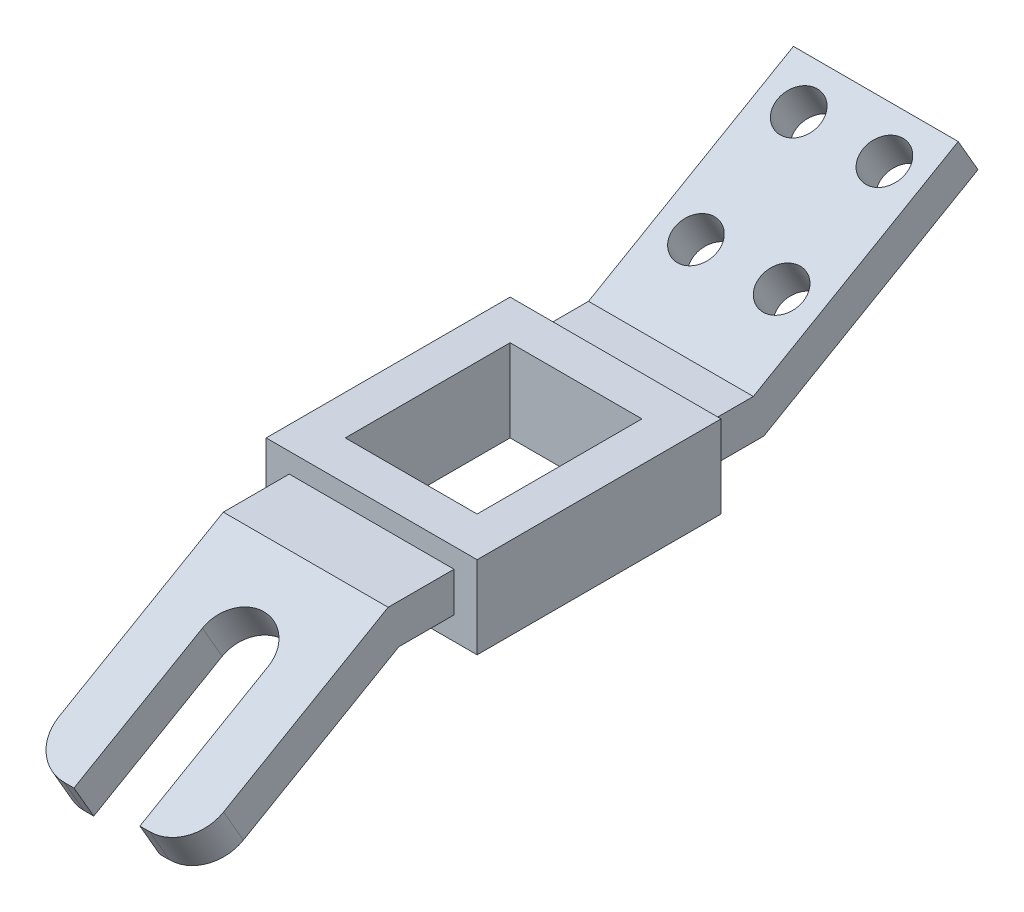
SolidWorks part; units mm, degrees
ref_plane "Alzado" through (0, 0, 0) normal (0, 0, 1) x (1, 0, 0)
ref_plane "Planta" through (0, 0, 0) normal (0, 1, 0) x (1, 0, 0)
ref_plane "Vista lateral" through (0, 0, 0) normal (1, 0, 0) x (0, 0, -1)
sketch "Croquis1" plane through (0, 0, 0) normal (0, 1, 0) x (1, 0, 0)
  line L1 (-32, 37) -> (32, 37)
  line L2 (-32, 37) -> (-32, -37)
  line L3 (-32, -37) -> (32, -37)
  line L4 (32, 37) -> (32, -37)
  line L5 (-20, 25) -> (20, 25)
  line L6 (-20, 25) -> (-20, -25)
  line L7 (-20, -25) -> (20, -25)
  line L8 (20, 25) -> (20, -25)
  point P4 (32, 0)
  point P5 (0, -37)
  point P11 (0, 25)
  point P12 (20, 0)
  dimension "D1" = 74
  dimension "D2" = 64
  dimension "D3" = 40
  dimension "D4" = 50
  dimension "D5" = 12
  dimension "D6" = 12
extrude "Saliente-Extruir2" add sketch "Croquis1" along normal blind 25
ref_plane "Plano1" through (0, 0, 0) normal (1, 0, 0) x (0, 0, -1)
sketch "Croquis2" plane through (0, 0, 0) normal (1, 0, 0) x (0, 0, -1)
  line L0 (37, 19) -> (53.7846, 19)
  line L1 (37, 25) -> (37, 0) construction
  line L2 (53.7846, 19) -> (115.9519, 54.8923)
  line L3 (115.9519, 54.8923) -> (121.9519, 44.5)
  line L4 (121.9519, 44.5) -> (57, 7)
  line L5 (57, 7) -> (37, 7)
  line L6 (-37, 25) -> (37, 25) construction
  line L7 (37, 19) -> (37, 7)
  line L8 (-37, 19) -> (-57, 19)
  line L9 (-37, 25) -> (-37, 0) construction
  line L10 (-57, 19) -> (-117.3124, -15.8214)
  line L11 (-117.3124, -15.8214) -> (-111.3124, -26.2137)
  line L12 (-111.3124, -26.2137) -> (-53.7846, 7)
  line L13 (-53.7846, 7) -> (-37, 7)
  line L14 (-37, 19) -> (-37, 7)
  dimension "D1" = 30
  dimension "D2" = 12
  dimension "D3" = 6
  dimension "D4" = 20
  dimension "D5" = 75
  dimension "D6" = 12
  dimension "D7" = 12
  dimension "D8" = 20
  dimension "D9" = 69.6428
  dimension "D10" = 30
  dimension "D11" = 12
extrude "Saliente-Extruir3" add sketch "Croquis2" along normal mid plane 50
sketch "Croquis3" plane through (0, -9.0394, -5.2189) normal (0, 0.866, 0.5) x (1, 0, 0)
  line L0 (-25, 127.8634) -> (-25, 56.0788) construction
  line L1 (25, 127.8634) -> (-25, 127.8634) construction
  circle A0 centre (-13, 115.8634) radius 6.5
  circle A1 centre (13, 115.8634) radius 6.5
  circle A2 centre (-13, 79.8634) radius 6.5
  circle A3 centre (13, 79.8634) radius 6.5
  point P2 (-8.3121, 105.529)
  point P3 (-12.7121, 116.608)
  point P4 (-4.8916, 104.0803)
  point P5 (-11.44, 114.6733)
  point P8 (0, 0)
  point P9 (7.645, 115.4825)
  point P14 (0, 0)
  point P15 (0, 0)
  dimension "D1" = 26
  dimension "D4" = 13
  dimension "D2" = 12
  dimension "D3" = 36
  dimension "D5" = 12
extrude "Cortar-Extruir1" cut sketch "Croquis3" against normal up to next
fillet "Redondeo1" radius 12 1 edges at (25, -21.0175, 114.3124)
fillet "Redondeo2" radius 12 1 edges at (-25, -21.0175, 114.3124)
sketch "Croquis5" plane through (0, 38.9317, 22.4772) normal (0, 0.866, 0.5) x (1, 0, 0)
  line L0 (13, -109.5062) -> (-13, -109.5062) construction
  line L1 (-10, -64.5062) -> (-10, -109.5062)
  line L2 (10, -64.5062) -> (10, -109.5062)
  line L3 (10, -109.5062) -> (-10, -109.5062)
  line L4 (25, -39.8634) -> (25, -97.5062) construction
  arc A0 (10, -64.5062) -> (-10, -64.5062) centre (0, -64.5062) ccw
  point P1 (0, 0)
  dimension "D1" = 20
  dimension "D2" = 45
  dimension "D3" = 25
extrude "Cortar-Extruir2" cut sketch "Croquis5" against normal up to next
